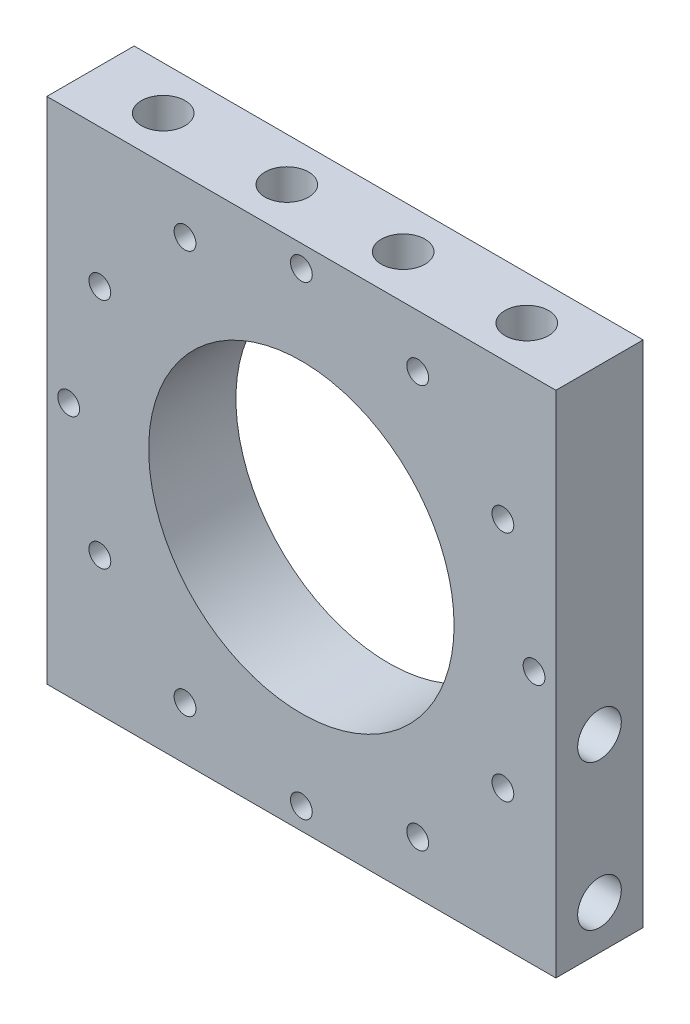
SolidWorks part; units mm, degrees
ref_plane "前视基准面" through (0, 0, 0) normal (0, 0, 1) x (1, 0, 0)
ref_plane "上视基准面" through (0, 0, 0) normal (0, 1, 0) x (1, 0, 0)
ref_plane "右视基准面" through (0, 0, 0) normal (1, 0, 0) x (0, 0, -1)
sketch "草图1" plane through (0, 0, 0) normal (0, 0, 1) x (1, 0, 0)
  line L0 (0, 37.7723) -> (0, 18.6396) construction
  line L1 (-35, -35) -> (35, -35)
  line L2 (-35, -35) -> (-35, 35)
  line L3 (-35, 35) -> (35, 35)
  line L4 (35, -35) -> (35, 35)
  line L5 (-35, -35) -> (35, 35) construction
  line L6 (-35, 35) -> (35, -35) construction
  line L8 (-35, 35) -> (35, 35) construction
  circle A4 centre (32, 0) radius 1.5
  circle A5 centre (27.7128, -16) radius 1.5
  circle A6 centre (16, -27.7128) radius 1.5
  circle A7 centre (0, -32) radius 1.5
  circle A8 centre (-16, -27.7128) radius 1.5
  circle A9 centre (-27.7128, -16) radius 1.5
  circle A10 centre (-32, 0) radius 1.5
  circle A11 centre (-27.7128, 16) radius 1.5
  circle A12 centre (-16, 27.7128) radius 1.5
  circle A13 centre (0, 32) radius 1.5
  circle A14 centre (16, 27.7128) radius 1.5
  circle A15 centre (27.7128, 16) radius 1.5
  circle A16 centre (0, 0) radius 21
  point P0 (0, 0)
  dimension "D3" = 42
  dimension "D8" = 3
  dimension "D1" = 70
  dimension "D2" = 70
  dimension "D9" = 32
  dimension "D10" = 12
extrude "凸台-拉伸1" add sketch "草图1" along normal blind 12
sketch "草图3" plane through (0, 35, 0) normal (0, 1, 0) x (1, 0, 0)
  line L0 (35, 0) -> (-35, 0) construction
  line L1 (-35, -12) -> (-35, 0) construction
  line L2 (0, -1.5275) -> (0, -9.0938) construction
  circle A0 centre (-25, -6) radius 3
  circle A1 centre (-8, -6) radius 3
  circle A2 centre (25, -6) radius 3
  circle A3 centre (8, -6) radius 3
  dimension "D1" = 6
  dimension "D2" = 6
  dimension "D5" = 17
  dimension "D3" = 6
  dimension "D4" = 10
  dimension "D6" = 6
extrude "切除-拉伸2" cut sketch "草图3" against normal blind 10
sketch "草图4" plane through (35, 0, 0) normal (1, 0, 0) x (0, 0, -1)
  line L0 (-12, -35) -> (0, -35) construction
  circle A0 centre (-6, -9) radius 3
  circle A1 centre (-6, -29) radius 3
  dimension "D1" = 6
  dimension "D2" = 6
  dimension "D3" = 6
  dimension "D4" = 20
extrude "切除-拉伸3" cut sketch "草图4" against normal blind 10
sketch "草图5" plane through (-35, 0, 0) normal (-1, 0, 0) x (0, 0, 1)
  line L0 (12, -35) -> (0, -35) construction
  circle A0 centre (6, -29) radius 3
  circle A1 centre (6, -9) radius 3
  dimension "D1" = 6
  dimension "D3" = 6
  dimension "D4" = 6
  dimension "D2" = 20
extrude "切除-拉伸4" cut sketch "草图5" against normal blind 10
sketch "草图6" plane through (0, -35, 0) normal (0, -1, 0) x (1, 0, 0)
  line L0 (-35, 0) -> (35, 0) construction
  line L1 (-35, 12) -> (-35, 0) construction
  line L2 (35, 12) -> (35, 0) construction
  circle A0 centre (10, 6) radius 3
  circle A1 centre (-10, 6) radius 3
  dimension "D1" = 6
  dimension "D2" = 6
  dimension "D3" = 6
  dimension "D4" = 6
  dimension "D5" = 25
  dimension "D6" = 25
extrude "切除-拉伸5" cut sketch "草图6" against normal blind 10
